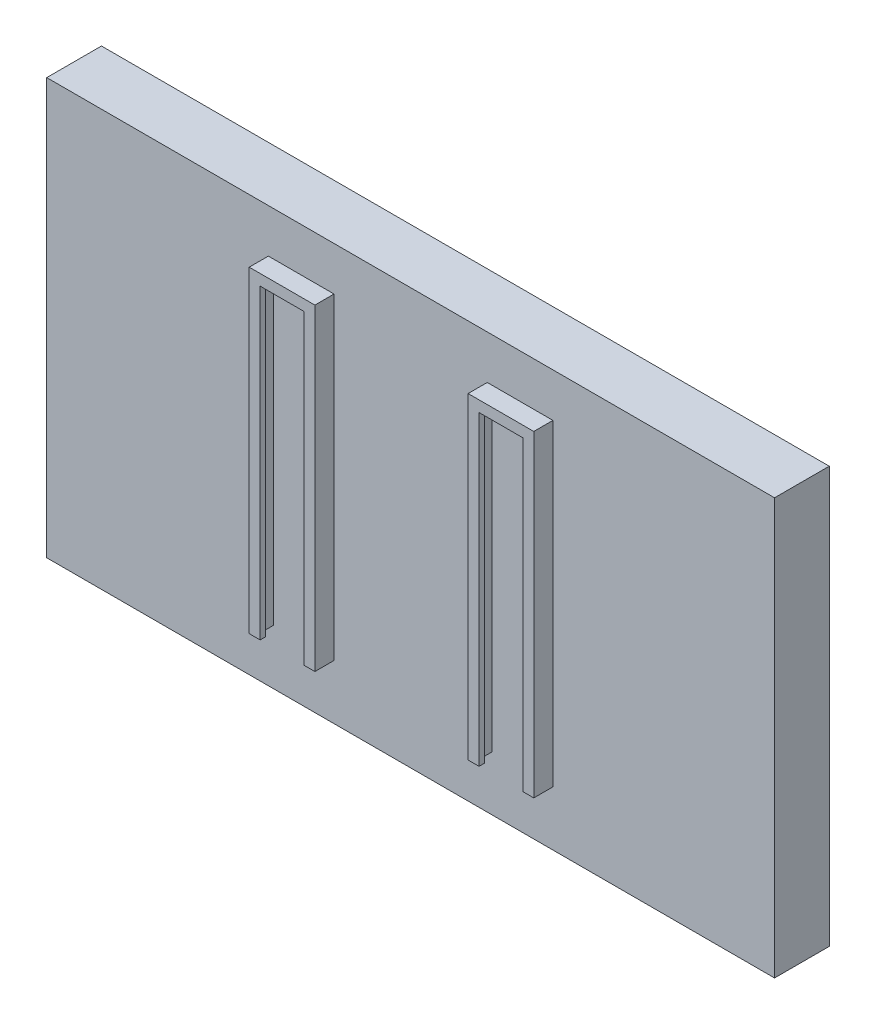
SolidWorks part; units mm, degrees
ref_plane "Alzado" through (0, 0, 0) normal (0, 0, 1) x (1, 0, 0)
ref_plane "Planta" through (0, 0, 0) normal (0, 1, 0) x (1, 0, 0)
ref_plane "Vista lateral" through (0, 0, 0) normal (1, 0, 0) x (0, 0, -1)
sketch "Croquis1" plane through (0, 0, 0) normal (0, 0, 1) x (1, 0, 0)
  line L1 (-66.5, 76) -> (66.5, 76)
  line L2 (-66.5, 76) -> (-66.5, 0)
  line L3 (-66.5, 0) -> (66.5, 0)
  line L4 (66.5, 76) -> (66.5, 0)
  dimension "D1" = 133
  dimension "D2" = 76
extrude "Saliente-Extruir1" add sketch "Croquis1" along normal blind 10
sketch "Croquis2" plane through (0, 0, 0) normal (0, 0, -1) x (-1, 0, 0)
  line L1 (-55, 70.5) -> (55, 70.5)
  line L2 (-55, 70.5) -> (-55, 5.5)
  line L3 (-55, 5.5) -> (55, 5.5)
  line L4 (55, 70.5) -> (55, 5.5)
  line L5 (-66.5, 0) -> (-66.5, 76) construction
  line L6 (-66.5, 76) -> (66.5, 76) construction
  dimension "D1" = 110
  dimension "D2" = 65
  dimension "D3" = 11.5
  dimension "D4" = 5.5
extrude "Cortar-Extruir1" cut sketch "Croquis2" against normal blind 2
sketch "Croquis3" plane through (0, 0, 10) normal (0, 0, 1) x (1, 0, 0)
  line L0 (0, 76) -> (0, 0) construction
  line L1 (66.5, 76) -> (-66.5, 76) construction
  line L2 (-20, 76) -> (-20, 0) construction
  line L3 (-66.5, 0) -> (66.5, 0) construction
  line L4 (20, 76) -> (20, 0) construction
  line L5 (16, 66) -> (14, 66)
  line L6 (-26, 10) -> (-24, 10)
  line L7 (-26, 10) -> (-26, 66)
  line L8 (-26, 66) -> (-24, 66)
  line L9 (-24, 10) -> (-24, 66)
  line L10 (-16, 66) -> (-14, 66)
  line L11 (-16, 66) -> (-16, 10)
  line L12 (-16, 10) -> (-14, 10)
  line L13 (-14, 66) -> (-14, 10)
  line L14 (16, 66) -> (16, 10)
  line L15 (14, 66) -> (14, 10)
  line L16 (16, 10) -> (14, 10)
  line L17 (26, 10) -> (24, 10)
  line L18 (26, 10) -> (26, 66)
  line L19 (26, 66) -> (24, 66)
  line L20 (24, 10) -> (24, 66)
  line L21 (26, 66) -> (26, 68)
  line L22 (-26, 66) -> (-14, 66)
  line L23 (-26, 66) -> (-26, 68)
  line L24 (-26, 68) -> (-14, 68)
  line L25 (-14, 66) -> (-14, 68)
  line L26 (14, 66) -> (14, 68)
  line L27 (26, 68) -> (14, 68)
  line L28 (26, 66) -> (14, 66)
  dimension "D1" = 20
  dimension "D2" = 20
  dimension "D3" = 2
  dimension "D4" = 2
  dimension "D5" = 8
  dimension "D6" = 4
  dimension "D7" = 10
  dimension "D8" = 10
  dimension "D9" = 2
extrude "Saliente-Extruir6" add sketch "Croquis3" along normal blind 3.5 contours L10 L25 L24 L23 L8 L22 | L6 L9 L8 L7 | L13 L10 L11 L12 | L16 L14 L5 L15 | L28 L19 L21 L27 L26 L5 | L20 L17 L18 L19
sketch "Croquis4" plane through (-24, 0, 0) normal (1, 0, 0) x (0, 0, -1)
  line L0 (-13.5, 10) -> (-10, 10) construction
  line L1 (-10, 66) -> (-12.5, 66)
  line L2 (-10, 66) -> (-10, 10)
  line L3 (-10, 10) -> (-12.5, 10)
  line L4 (-12.5, 66) -> (-12.5, 10)
  line L5 (-13.5, 66) -> (-10, 66) construction
  line L8 (-10, 10) -> (-10, 66) construction
  dimension "D1" = 2.5
extrude "Cortar-Extruir2" cut sketch "Croquis4" against normal blind 1.1
sketch "Croquis5" plane through (-16, 0, 0) normal (-1, 0, 0) x (0, 0, 1)
  line L0 (13.5, 66) -> (10, 66) construction
  line L1 (10, 66) -> (12.5, 66)
  line L2 (10, 66) -> (10, 10)
  line L3 (10, 10) -> (12.5, 10)
  line L4 (12.5, 66) -> (12.5, 10)
  line L5 (13.5, 10) -> (10, 10) construction
  line L7 (10, 66) -> (10, 10) construction
  dimension "D1" = 2.5
extrude "Cortar-Extruir3" cut sketch "Croquis5" against normal blind 1.1
sketch "Croquis6" plane through (16, 0, 0) normal (1, 0, 0) x (0, 0, -1)
  line L0 (-13.5, 66) -> (-10, 66) construction
  line L1 (-12.5, 66) -> (-10, 66)
  line L2 (-12.5, 66) -> (-12.5, 10)
  line L3 (-12.5, 10) -> (-10, 10)
  line L4 (-10, 66) -> (-10, 10)
  line L6 (-13.5, 10) -> (-10, 10) construction
  line L7 (-10, 66) -> (-10, 10) construction
  dimension "D1" = 2.5
extrude "Cortar-Extruir4" cut sketch "Croquis6" against normal blind 1.1
sketch "Croquis7" plane through (24, 0, 0) normal (-1, 0, 0) x (0, 0, 1)
  line L0 (13.5, 66) -> (10, 66) construction
  line L1 (10, 66) -> (12.5, 66)
  line L2 (10, 66) -> (10, 10)
  line L3 (10, 10) -> (12.5, 10)
  line L4 (12.5, 66) -> (12.5, 10)
  line L6 (13.5, 10) -> (10, 10) construction
  line L7 (10, 10) -> (10, 66) construction
  dimension "D1" = 2.5
extrude "Cortar-Extruir5" cut sketch "Croquis7" against normal blind 1.1
